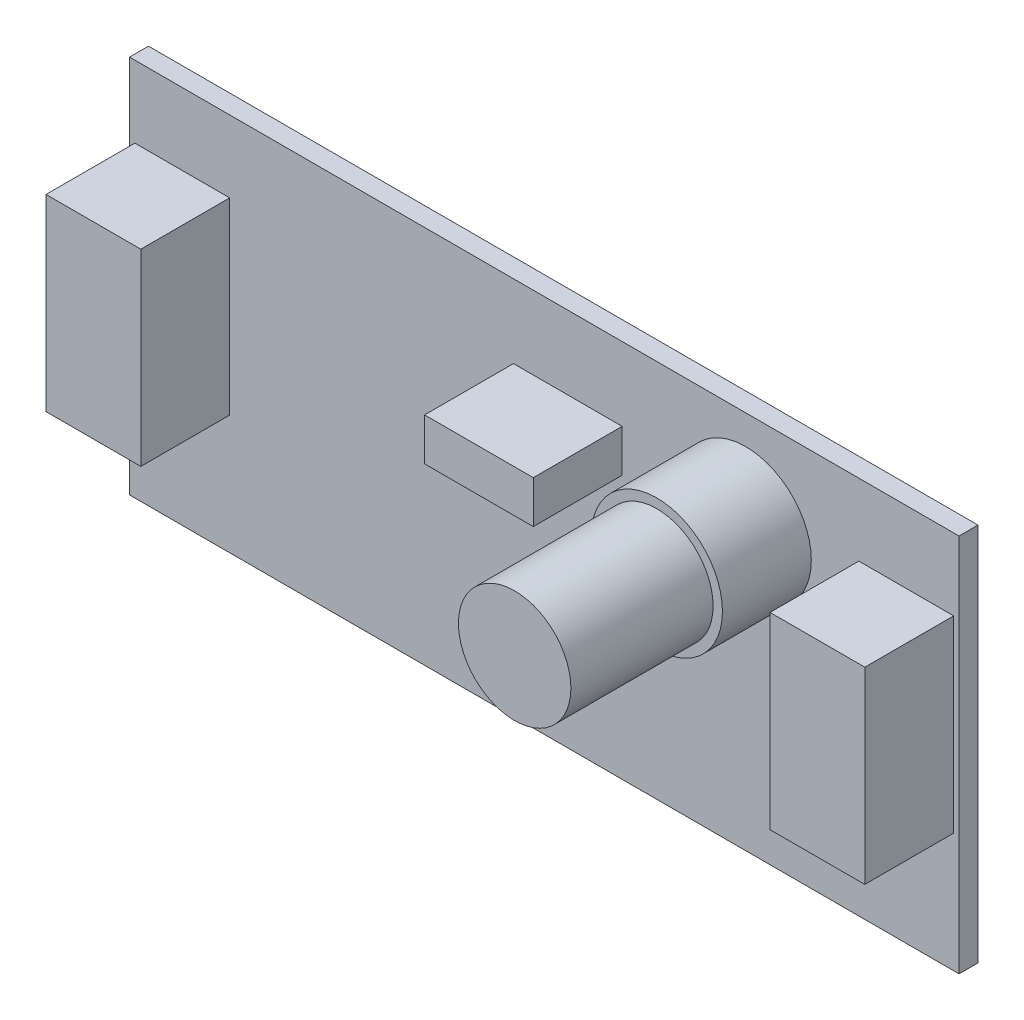
SolidWorks part; units mm, degrees
ref_plane "Front Plane" through (0, 0, 0) normal (0, 0, 1) x (1, 0, 0)
ref_plane "Top Plane" through (0, 0, 0) normal (0, 1, 0) x (1, 0, 0)
ref_plane "Right Plane" through (0, 0, 0) normal (1, 0, 0) x (0, 0, -1)
sketch "Model" plane through (0, 0, 0) normal (0, 0, 1) x (1, 0, 0)
  line L0 (0, 31.9999) -> (69.9999, 31.9999)
  line L1 (69.9999, 31.9999) -> (69.9999, 0)
  line L2 (69.9999, 0) -> (0, 0)
  line L3 (0, 0) -> (0, 31.9989)
  line L4 (46.6737, 17.0786) -> (45.2388, 17.0786)
  line L5 (45.2388, 17.0786) -> (45.2388, 13.9214)
  line L6 (45.2388, 13.9214) -> (46.6737, 13.9214)
  line L7 (50.3261, 17.0786) -> (51.761, 17.0786)
  line L8 (51.761, 17.0786) -> (51.761, 13.9214)
  line L9 (51.761, 13.9214) -> (50.3261, 13.9214)
  line L10 (0.452, 24.2188) -> (0.452, 11.8)
  line L11 (4.0812, 10.062) -> (10.104, 10.062)
  line L12 (10.104, 10.062) -> (10.104, 11.078)
  line L13 (10.104, 11.078) -> (8.453, 11.078)
  line L14 (8.453, 11.078) -> (8.453, 12.0188)
  line L15 (4.0812, 25.9379) -> (10.104, 25.9379)
  line L16 (10.104, 25.9379) -> (10.104, 24.9219)
  line L17 (10.104, 24.9219) -> (8.453, 24.9219)
  line L18 (8.453, 24.9219) -> (8.453, 23.9811)
  line L19 (44.8417, 18.6737) -> (43.1581, 18.6737)
  line L20 (44.8417, 20.3262) -> (43.1581, 20.3262)
  line L21 (44.8417, 18.6737) -> (44.8417, 20.3262)
  line L22 (69.5478, 11.7811) -> (69.5478, 24.2)
  line L23 (65.9187, 25.9379) -> (59.8959, 25.9379)
  line L24 (59.8959, 25.9379) -> (59.8959, 24.9219)
  line L25 (59.8959, 24.9219) -> (61.5469, 24.9219)
  line L26 (61.5469, 24.9219) -> (61.5469, 23.9811)
  line L27 (65.9187, 10.062) -> (59.8959, 10.062)
  line L28 (59.8959, 10.062) -> (59.8959, 11.078)
  line L29 (59.8959, 11.078) -> (61.5469, 11.078)
  line L30 (61.5469, 11.078) -> (61.5469, 12.0188)
  line L31 (16.4262, 10.3394) -> (17.3851, 10.3394)
  line L32 (17.3851, 10.3394) -> (17.3851, 11.6606)
  line L33 (17.3851, 11.6606) -> (16.4262, 11.6606)
  line L34 (15.5738, 10.3394) -> (14.6149, 10.3394)
  line L35 (14.6149, 10.3394) -> (14.6149, 11.6606)
  line L36 (14.6149, 11.6606) -> (15.5738, 11.6606)
  line L37 (26.4262, 10.3394) -> (27.385, 10.3394)
  line L38 (27.385, 10.3394) -> (27.385, 11.6606)
  line L39 (27.385, 11.6606) -> (26.4262, 11.6606)
  line L40 (25.5737, 10.3394) -> (24.6149, 10.3394)
  line L41 (24.6149, 10.3394) -> (24.6149, 11.6606)
  line L42 (24.6149, 11.6606) -> (25.5737, 11.6606)
  line L43 (26.4262, 28.3393) -> (27.385, 28.3393)
  line L44 (27.385, 28.3393) -> (27.385, 29.6605)
  line L45 (27.385, 29.6605) -> (26.4262, 29.6605)
  line L46 (25.5737, 28.3393) -> (24.6149, 28.3393)
  line L47 (24.6149, 28.3393) -> (24.6149, 29.6605)
  line L48 (24.6149, 29.6605) -> (25.5737, 29.6605)
  line L49 (16.4262, 28.3393) -> (17.3851, 28.3393)
  line L50 (17.3851, 28.3393) -> (17.3851, 29.6605)
  line L51 (17.3851, 29.6605) -> (16.4262, 29.6605)
  line L52 (15.5738, 28.3393) -> (14.6149, 28.3393)
  line L53 (14.6149, 28.3393) -> (14.6149, 29.6605)
  line L54 (14.6149, 29.6605) -> (15.5738, 29.6605)
  line L55 (34.4599, 23.4921) -> (34.4599, 24.5081)
  line L56 (34.4599, 24.5081) -> (35.4759, 24.5081)
  line L57 (35.4759, 24.5081) -> (35.4759, 23.4921)
  line L58 (35.4759, 23.4921) -> (34.4599, 23.4921)
  line L59 (33.9519, 22.7301) -> (33.9519, 25.2701)
  line L60 (33.9519, 25.2701) -> (40.0479, 25.2701)
  line L61 (40.0479, 25.2701) -> (40.0479, 22.7301)
  line L62 (40.0479, 22.7301) -> (33.9519, 22.7301)
  line L63 (32.4, 25.8001) -> (33.6744, 25.8001)
  line L64 (35.3255, 25.8001) -> (36.1744, 25.8001)
  line L65 (37.8255, 25.8001) -> (38.6744, 25.8001)
  line L66 (40.3255, 25.8001) -> (41.5719, 25.778)
  line L67 (41.5719, 22.2221) -> (40.3194, 22.2221)
  line L68 (38.6805, 22.2221) -> (37.8194, 22.2221)
  line L69 (36.1805, 22.2221) -> (35.3194, 22.2221)
  line L70 (33.6805, 22.2221) -> (32.4, 22.2221)
  line L71 (32.4, 25.8001) -> (32.4, 22.222)
  line L72 (41.5719, 22.2221) -> (41.5719, 25.8001)
  line L73 (34.9785, 17.5762) -> (38.0213, 17.5762)
  line L74 (38.0213, 17.5762) -> (38.0213, 12.4238)
  line L75 (38.0213, 12.4238) -> (34.9785, 12.4238)
  line L76 (34.9785, 12.4238) -> (34.9785, 17.5762)
  line L77 (17.5612, 7.0988) -> (17.5612, 8.9012)
  line L78 (14.4388, 7.0988) -> (14.4388, 8.9012)
  line L79 (27.5612, 7.0988) -> (27.5612, 8.9012)
  line L80 (24.4387, 7.0988) -> (24.4387, 8.9012)
  line L81 (27.5612, 25.0988) -> (27.5612, 26.9011)
  line L82 (24.4387, 25.0988) -> (24.4387, 26.9011)
  line L83 (17.5612, 25.0988) -> (17.5612, 26.9011)
  line L84 (14.4388, 25.0988) -> (14.4388, 26.9011)
  line L85 (52.2175, 2.7987) -> (48.7737, 2.7987)
  line L86 (48.7737, 2.7987) -> (48.7737, 9.465)
  line L87 (48.7737, 9.465) -> (50.5099, 11.2012)
  line L88 (50.5099, 11.2012) -> (52.2175, 11.2012)
  line L89 (53.7823, 2.7987) -> (57.2261, 2.7987)
  line L90 (57.2261, 2.7987) -> (57.2261, 9.465)
  line L91 (57.2261, 9.465) -> (55.4899, 11.2012)
  line L92 (55.4899, 11.2012) -> (53.7823, 11.2012)
  line L93 (42.2175, 2.7987) -> (38.7737, 2.7987)
  line L94 (38.7737, 2.7987) -> (38.7737, 9.465)
  line L95 (38.7737, 9.465) -> (40.51, 11.2012)
  line L96 (40.51, 11.2012) -> (42.2175, 11.2012)
  line L97 (43.7823, 2.7987) -> (47.2261, 2.7987)
  line L98 (47.2261, 2.7987) -> (47.2261, 9.465)
  line L99 (47.2261, 9.465) -> (45.4899, 11.2012)
  line L100 (45.4899, 11.2012) -> (43.7823, 11.2012)
  line L101 (61.4261, 8.5636) -> (58.5737, 8.5636)
  line L102 (58.4213, 8.4112) -> (58.4213, 6.7762)
  line L103 (61.5785, 6.7762) -> (61.5785, 8.4112)
  line L104 (58.4213, 3.5888) -> (58.4213, 5.2238)
  line L105 (61.5785, 5.2238) -> (61.5785, 3.5888)
  line L106 (61.4261, 3.4364) -> (58.5737, 3.4364)
  line L107 (65.4261, 8.5636) -> (62.5737, 8.5636)
  line L108 (62.4213, 8.4112) -> (62.4213, 6.7762)
  line L109 (65.5785, 6.7762) -> (65.5785, 8.4112)
  line L110 (62.4213, 3.5888) -> (62.4213, 5.2238)
  line L111 (65.5785, 5.2238) -> (65.5785, 3.5888)
  line L112 (65.4261, 3.4364) -> (62.5737, 3.4364)
  line L113 (40.3101, 15.254) -> (40.3101, 13.2894) construction
  arc A0 (50.7299, 28.572) -> (47.4619, 25.3866) centre (51.9999, 24) ccw
  arc A1 (47.4279, 22.603) -> (50.6029, 19.4281) centre (51.9998, 24.0001) ccw
  arc A2 (53.3969, 19.428) -> (56.5966, 22.6866) centre (51.9998, 24.0001) ccw
  arc A3 (56.5719, 25.27) -> (53.3866, 28.5381) centre (51.9998, 24.0001) ccw
  arc A4 (51.1109, 29.461) -> (46.5389, 24.889) centre (51.9998, 24.0001) ccw
  arc A5 (46.5389, 23.111) -> (51.1109, 18.5392) centre (51.9998, 24.0001) ccw
  arc A6 (52.8889, 18.539) -> (57.4609, 23.111) centre (51.9998, 24.0001) ccw
  arc A7 (57.4609, 24.889) -> (52.8889, 29.4612) centre (51.9998, 24.0001) ccw
  arc A8 (61.5785, 8.4112) -> (61.4261, 8.5636) centre (61.4261, 8.4112) ccw
  arc A9 (58.5737, 8.5636) -> (58.4213, 8.4112) centre (58.5737, 8.4112) ccw
  arc A10 (61.4261, 3.4364) -> (61.5785, 3.5888) centre (61.4261, 3.5888) ccw
  arc A11 (58.4213, 3.5888) -> (58.5737, 3.4364) centre (58.5737, 3.5888) ccw
  arc A12 (65.5785, 8.4112) -> (65.4261, 8.5636) centre (65.4261, 8.4112) ccw
  arc A13 (62.5737, 8.5636) -> (62.4213, 8.4112) centre (62.5737, 8.4112) ccw
  arc A14 (65.4261, 3.4364) -> (65.5785, 3.5888) centre (65.4261, 3.5888) ccw
  arc A15 (62.4213, 3.5888) -> (62.5737, 3.4364) centre (62.5737, 3.5888) ccw
  circle A16 centre (35.7307, 16.905) radius 0.1501
  circle A17 centre (33.8176, 17.6723) radius 0.1501
  circle A18 centre (14.3317, 6.7026) radius 0.1501
  circle A19 centre (24.3317, 6.7026) radius 0.1501
  circle A20 centre (24.3317, 24.7025) radius 0.1501
  circle A21 centre (14.3317, 24.7025) radius 0.1501
  circle A22 centre (47.4998, 24.0001) radius 0.7671
  circle A23 centre (47.5, 24) radius 1.125
  circle A24 centre (51.9998, 28.5001) radius 0.7671
  circle A25 centre (51.9999, 28.4998) radius 1.125
  circle A26 centre (56.4998, 24.0001) radius 0.7671
  circle A27 centre (56.5, 24) radius 1.125
  circle A28 centre (51.9998, 19.5001) radius 0.7671
  circle A29 centre (51.9999, 19.4998) radius 1.125
  circle A30 centre (51.9999, 24) radius 0.6671
  circle A31 centre (52.0001, 23.9997) radius 0.975
  text T0 "BACKLIGHT" font "ARIAL" height 1.143
  text T1 "D1" font "ARIAL" height 1.143
  text T2 "MOTHERBOARD" font "ARIAL" height 1.143
  text T3 "SW1" font "ARIAL" height 1.143
  text T4 "U1" font "ARIAL" height 1.143
  text T5 "U8" font "ARIAL" height 1.143
  text T6 "C1" font "ARIAL" height 1.143
  text T7 "C2" font "ARIAL" height 1.143
  text T8 "C4" font "ARIAL" height 1.143
  text T9 "C6" font "ARIAL" height 1.143
sketch "Sketch2" plane through (0, 0, 0) normal (0, 0, 1) x (1, 0, 0)
  line L1 (0, 31.9999) -> (69.9999, 31.9999)
  line L2 (0, 31.9999) -> (0, 0)
  line L3 (0, 0) -> (69.9999, 0)
  line L4 (69.9999, 31.9999) -> (69.9999, 0)
extrude "Boss-Extrude1" add sketch "Sketch2" against normal blind 1.6
sketch "Sketch3" plane through (0, 0, 0) normal (0, 0, 1) x (1, 0, 0)
  line L0 (65.9187, 10.062) -> (59.8959, 10.062) construction
  line L1 (69.5478, 25.9379) -> (61.5469, 25.9379)
  line L2 (69.5478, 25.9379) -> (69.5478, 10.062)
  line L3 (69.5478, 10.062) -> (61.5469, 10.062)
  line L4 (61.5469, 25.9379) -> (61.5469, 10.062)
  line L5 (4.0812, 10.062) -> (10.104, 10.062) construction
  line L6 (0.452, 25.9379) -> (8.453, 25.9379)
  line L7 (0.452, 25.9379) -> (0.452, 10.062)
  line L8 (0.452, 10.062) -> (8.453, 10.062)
  line L9 (8.453, 25.9379) -> (8.453, 10.062)
  line L10 (65.9187, 25.9379) -> (59.8959, 25.9379) construction
  line L11 (69.5478, 11.7811) -> (69.5478, 24.2) construction
  line L12 (61.5469, 24.9219) -> (61.5469, 23.9811) construction
  line L13 (4.0812, 25.9379) -> (10.104, 25.9379) construction
  line L14 (0.452, 24.2188) -> (0.452, 11.8) construction
  line L15 (8.453, 24.9219) -> (8.453, 23.9811) construction
  line L17 (32.4, 25.8001) -> (41.5719, 25.8001)
  line L18 (32.4, 25.8001) -> (32.4, 22.2221)
  line L19 (32.4, 22.2221) -> (41.5719, 22.2221)
  line L20 (41.5719, 25.8001) -> (41.5719, 22.2221)
  circle A0 centre (51.9999, 24) radius 5.5332
extrude "Boss-Extrude2" add sketch "Sketch3" along normal blind 7.5
sketch "Sketch4" plane through (0, 0, 7.5) normal (0, 0, 1) x (1, 0, 0)
  circle A0 centre (51.9999, 24) radius 4.745
extrude "Boss-Extrude3" add sketch "Sketch4" along normal blind 12
